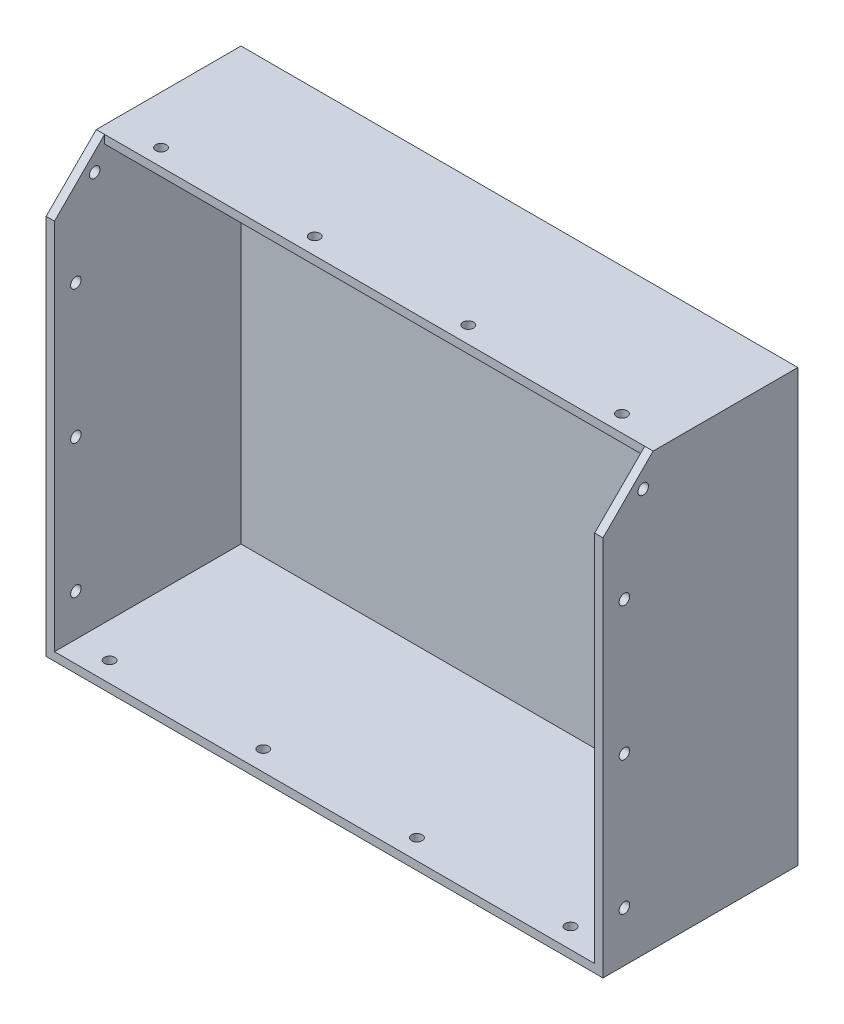
SolidWorks part; units mm, degrees
material "Custom Plastic"
ref_plane "X-Y Datum" through (0, 0, 0) normal (0, 0, 1) x (1, 0, 0)
ref_plane "X-Z Datum" through (0, 0, 0) normal (0, 1, 0) x (1, 0, 0)
ref_plane "Y-Z Datum" through (0, 0, 0) normal (1, 0, 0) x (0, 0, -1)
sketch "Sketch2" plane through (0, 0, 0) normal (0, 0, 1) x (1, 0, 0)
  line L1 (-105.8757, -82) -> (105.8757, -82)
  line L2 (-105.8757, -82) -> (-105.8757, 82)
  line L3 (-105.8757, 82) -> (105.8757, 82)
  line L4 (105.8757, -82) -> (105.8757, 82)
  line L5 (-105.8757, -82) -> (105.8757, 82) construction
  line L6 (-105.8757, 82) -> (105.8757, -82) construction
  point P0 (0, 0)
extrude "Boss-Extrude1" add sketch "Sketch2" along normal blind 74.0833
sketch "Sketch9" plane through (0, 0, 74.0833) normal (0, 0, 1) x (1, 0, 0)
  line L0 (-105.8757, -47.7482) -> (-102.7007, -47.7482)
  line L1 (-105.8757, 82) -> (-105.8757, -82) construction
  line L2 (-61.2665, -82) -> (-61.2665, -78.825)
  line L3 (-105.8757, -82) -> (105.8757, -82) construction
  line L4 (105.8757, -21.963) -> (102.7007, -21.963)
  line L5 (105.8757, -82) -> (105.8757, 82) construction
  line L6 (-87.7618, 82) -> (-87.7618, 78.825)
  line L7 (105.8757, 82) -> (-105.8757, 82) construction
  line L8 (-102.7007, 62.95) -> (-102.7007, 78.825)
  line L9 (-102.7007, -82) -> (-102.7007, 62.95)
  line L10 (-61.2665, -78.825) -> (-102.7007, -78.825)
  line L11 (-61.2665, -78.825) -> (102.7007, -78.825)
  line L12 (102.7007, -78.825) -> (102.7007, 82)
  line L13 (-102.7007, 78.825) -> (102.7007, 78.825)
extrude "Cut-Extrude7" cut sketch "Sketch9" against normal blind 70.9083
sketch "Sketch11" plane through (-105.8757, 0, 0) normal (-1, 0, 0) x (0, 0, 1)
  line L0 (74.0833, 62.95) -> (55.0333, 62.95)
  line L1 (74.0833, 82) -> (74.0833, -82) construction
  line L2 (55.0333, 62.95) -> (55.0333, 82)
  line L3 (74.0833, 82) -> (0, 82) construction
  line L4 (55.0333, 82) -> (74.0833, 62.95)
  line L5 (55.0333, 82) -> (74.0833, 82)
  line L6 (74.0833, 82) -> (74.0833, 62.95)
  line L7 (55.0333, 79.6238) -> (58.2083, 79.6238)
  line L8 (58.2083, 78.825) -> (58.2083, 82)
  line M5 (74.0833, -82) -> (74.0833, 82)
  line M6 (74.0833, 82) -> (0, 82)
extrude "Cut-Extrude9" cut sketch "Sketch11" against normal up to next contours L8 L4 M5 M6
sketch "Sketch13" plane through (-105.8757, 0, 0) normal (-1, 0, 0) x (0, 0, 1)
  line L0 (58.2083, 78.825) -> (55.0333, 82)
  line L1 (58.2083, 82) -> (0, 82) construction
  line L2 (55.0333, 82) -> (58.2083, 82)
  line L3 (58.2083, 82) -> (58.2083, 78.825)
extrude "Cut-Extrude10" cut sketch "Sketch13" against normal blind 3.175
sketch "Sketch14" plane through (0, 0, 58.2083) normal (0, 0, 1) x (1, 0, 0)
  line L1 (-102.7007, 82) -> (102.7007, 82)
  line L2 (-102.7007, 82) -> (-102.7007, 78.825)
  line L3 (-102.7007, 78.825) -> (102.7007, 78.825)
  line L4 (102.7007, 82) -> (102.7007, 78.825)
extrude "Cut-Extrude11" cut sketch "Sketch14" against normal blind 3.175
sketch "Sketch15" plane through (105.8757, 0, 0) normal (1, 0, 0) x (0, 0, -1)
  line L0 (-58.2083, 78.825) -> (-55.0333, 82)
  line L1 (-55.0333, 82) -> (-58.2083, 82)
  line L2 (-58.2083, 82) -> (-58.2083, 79.2157)
  line L3 (-58.2083, 82) -> (-58.2083, 78.825) construction
extrude "Cut-Extrude12" cut sketch "Sketch15" against normal blind 3.175 and the other way through all
sketch "Sketch16" plane through (-105.8757, 0, 0) normal (-1, 0, 0) x (0, 0, 1)
  line L0 (65.9553, -68.9821) -> (74.0833, -68.9821)
  line L2 (74.0833, 62.95) -> (74.0833, -82) construction
  line L3 (65.9553, -82) -> (65.9553, -62.95)
  line L4 (74.0833, -82) -> (0, -82) construction
  circle A0 centre (65.9553, -62.95) radius 2
  dimension "D1" = 8.128
  dimension "D2" = 19.05
extrude "Cut-Extrude13" cut sketch "Sketch16" against normal through all
pattern_linear "LPattern1" count 3 spacing 50.8 along (0, 1, 0) of "Cut-Extrude13"
sketch "Sketch18" plane through (0, -82, 0) normal (0, -1, 0) x (1, 0, 0)
  line L0 (-89.3657, 74.0833) -> (-89.3657, 66.4633)
  line L1 (-105.8757, 74.0833) -> (105.8757, 74.0833) construction
  line L2 (-89.3657, 66.4633) -> (-105.8757, 66.4633)
  line L3 (-105.8757, 74.0833) -> (-105.8757, 0) construction
  circle A0 centre (-89.3657, 66.4633) radius 2
  dimension "D1" = 7.62
  dimension "D2" = 16.51
extrude "Cut-Extrude14" cut sketch "Sketch18" against normal up to next contours A0
pattern_linear "LPattern2" count 4 spacing 58.42 along (1, 0, 0) of "Cut-Extrude14"
sketch "Sketch19" plane through (0, 82, 0) normal (0, 1, 0) x (1, 0, 0)
  line L0 (-105.8757, -48.6833) -> (-87.5877, -48.6833)
  line L1 (-105.8757, -55.0333) -> (-105.8757, 0) construction
  line L2 (-96.7317, -48.6833) -> (-96.7317, -55.0333)
  line L3 (102.7007, -55.0333) -> (-102.7007, -55.0333) construction
  circle A0 centre (-87.5877, -48.6833) radius 2
  dimension "D1" = 18.288
  dimension "D2" = 6.35
extrude "Cut-Extrude15" cut sketch "Sketch19" against normal up to next
pattern_linear "LPattern3" count 4 spacing 58.42 along (1, 0, 0) of "Cut-Extrude15"
sketch "Sketch20" plane through (-105.8757, 0, 0) normal (-1, 0, 0) x (0, 0, 1)
  line L2 (62.2175, 74.8158) -> (58.805, 71.4033)
  line L3 (55.0333, 82) -> (74.0833, 62.95) construction
  line L4 (62.2175, 74.8158) -> (55.0333, 82)
  circle A0 centre (58.805, 71.4033) radius 2
  dimension "D1" = 4.826
  dimension "D2" = 10.16
extrude "Cut-Extrude16" cut sketch "Sketch20" against normal through all
